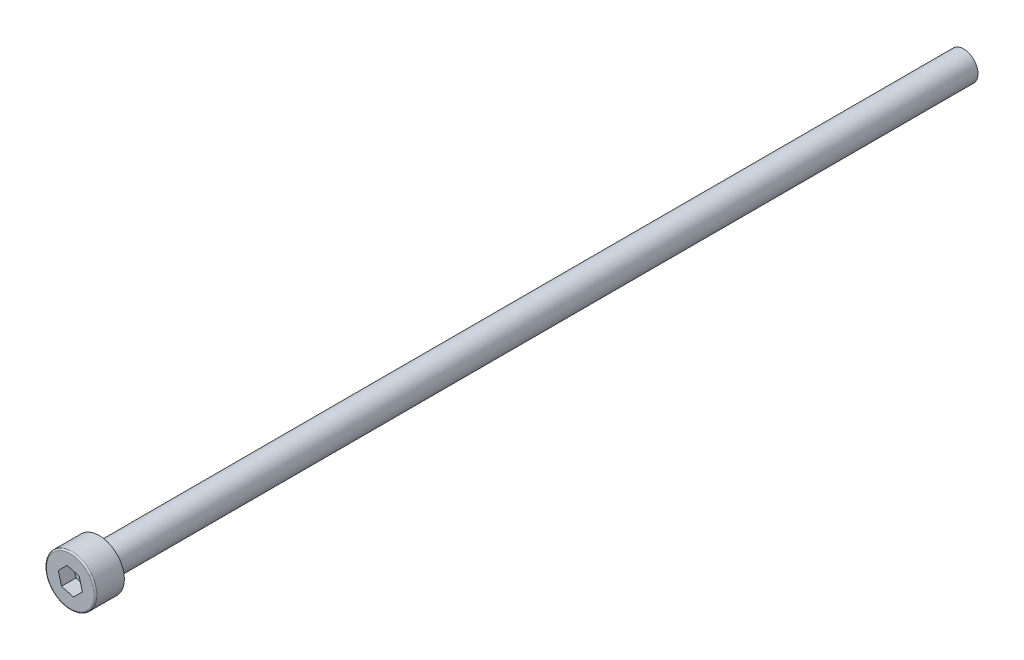
SolidWorks part; units mm, degrees
ref_plane "前视基准面" through (0, 0, 0) normal (0, 0, 1) x (1, 0, 0)
ref_plane "上视基准面" through (0, 0, 0) normal (0, 1, 0) x (1, 0, 0)
ref_plane "右视基准面" through (0, 0, 0) normal (1, 0, 0) x (0, 0, -1)
sketch "草图1" plane through (0, 0, 0) normal (0, 0, 1) x (1, 0, 0)
  circle A0 centre (0, 0) radius 3.5
  dimension "D1" = 7
extrude "凸台-拉伸1" add sketch "草图1" along normal blind 4
sketch "草图2" plane through (0, 0, 4) normal (0, 0, 1) x (1, 0, 0)
  line L1 (-1.2247, -1.2247) -> (0.4483, -1.673)
  line L2 (0.4483, -1.673) -> (1.673, -0.4483)
  line L3 (1.673, -0.4483) -> (1.2247, 1.2247)
  line L4 (1.2247, 1.2247) -> (-0.4483, 1.673)
  line L5 (-0.4483, 1.673) -> (-1.673, 0.4483)
  line L6 (-1.673, 0.4483) -> (-1.2247, -1.2247)
  circle A0 centre (0, 0) radius 1.5 construction
  dimension "D1" = 3
extrude "切除-拉伸1" cut sketch "草图2" against normal blind 2
sketch "草图3" plane through (0, 0, 0) normal (0, 0, -1) x (-1, 0, 0)
  circle A0 centre (0, 0) radius 2
  dimension "D1" = 4
extrude "凸台-拉伸2" add sketch "草图3" along normal blind 120
fillet "圆角1" radius 0.2 1 edges at (3.5, 0, 4)
